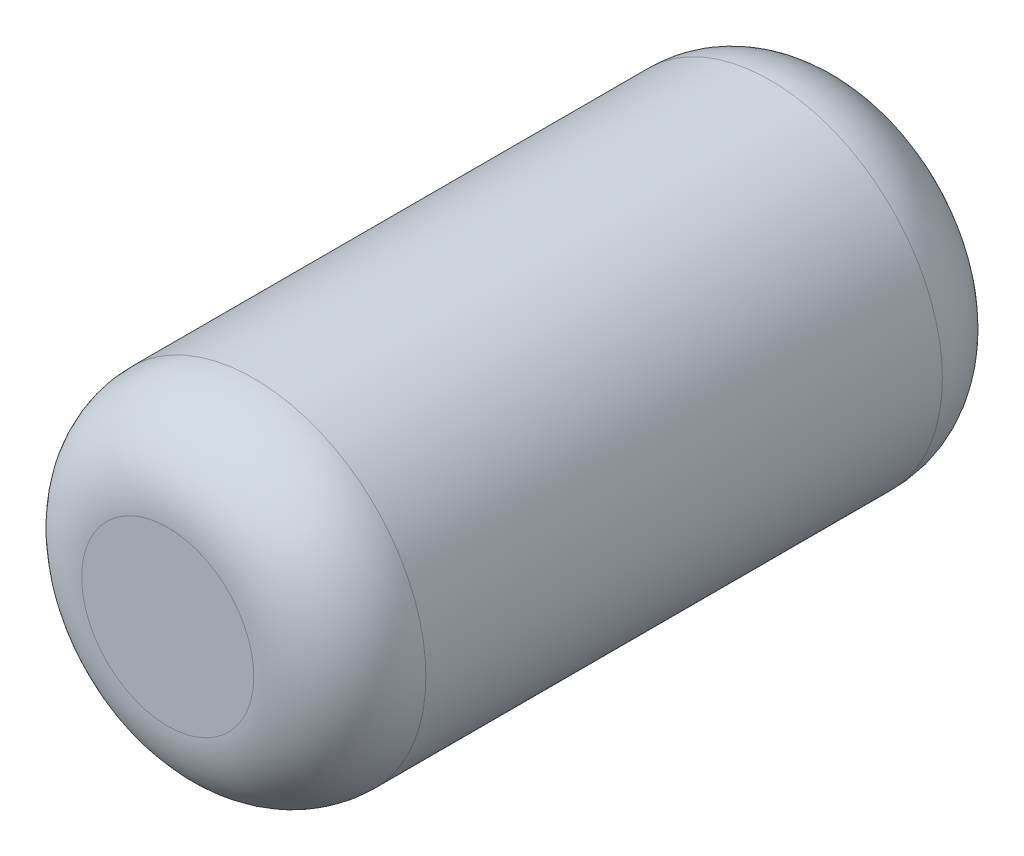
SolidWorks part; units mm, degrees
ref_plane "Front Plane" through (0, 0, 0) normal (0, 0, 1) x (1, 0, 0)
ref_plane "Top Plane" through (0, 0, 0) normal (0, 1, 0) x (1, 0, 0)
ref_plane "Right Plane" through (0, 0, 0) normal (1, 0, 0) x (0, 0, -1)
sketch "Sketch2" plane through (0, 0, 0) normal (0, 0, 1) x (1, 0, 0)
  circle A0 centre (0, 0) radius 50
  dimension "D1" = 100
extrude "Boss-Extrude1" add sketch "Sketch2" along normal mid plane 200
fillet "Fillet1" radius 25 2 edges at (50, 0, -100) (50, 0, 100)
